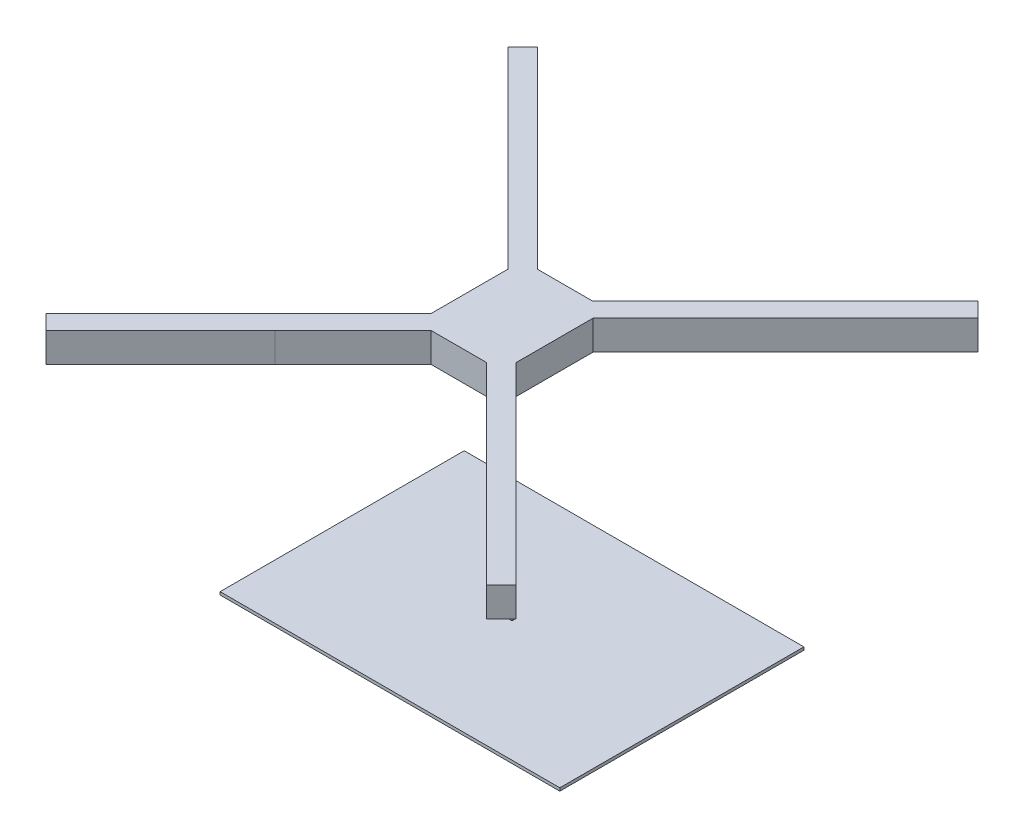
SolidWorks part; units mm, degrees
material "1060 Alloy"
ref_plane "Front" through (0, 0, 0) normal (0, 0, 1) x (1, 0, 0)
ref_plane "Top" through (0, 0, 0) normal (0, 1, 0) x (1, 0, 0)
ref_plane "Right" through (0, 0, 0) normal (1, 0, 0) x (0, 0, -1)
sketch "Sketch1" plane through (0, 0, 0) normal (0, 1, 0) x (1, 0, 0)
  line L0 (-37.7393, 72.1741) -> (-143.8053, 178.2401)
  line L5 (57.7393, -72.1741) -> (-57.7393, 72.1741) construction
  line L6 (57.7393, 72.1741) -> (-57.7393, -72.1741) construction
  line L8 (-163.8023, 158.2431) -> (-57.7393, 52.1741)
  line L9 (37.7393, 72.1741) -> (143.8053, 178.2401)
  line L11 (163.8023, 158.2431) -> (57.7393, 52.1741)
  line L12 (37.7393, -72.1741) -> (143.8053, -178.2401)
  line L14 (163.8023, -158.2431) -> (57.7393, -52.1741)
  line L15 (-57.7393, -52.1741) -> (-163.8023, -158.2431)
  line L17 (-143.8053, -178.2401) -> (-37.7393, -72.1741)
  line L18 (-57.7393, -52.1741) -> (-57.7393, 52.1741)
  line L19 (37.7393, 72.1741) -> (-37.7393, 72.1741)
  line L20 (-37.7393, -72.1741) -> (37.7393, -72.1741)
  line L21 (57.7393, 52.1741) -> (57.7393, -52.1741)
  line L34 (143.8053, -178.2401) -> (299.3688, -333.8036)
  line L35 (299.3688, -333.8036) -> (319.3658, -313.8066)
  line L36 (319.3658, -313.8066) -> (163.8023, -158.2431)
  line L37 (-163.8023, -158.2431) -> (-319.3613, -313.8111)
  line L38 (-319.3613, -313.8111) -> (-299.3638, -333.8075)
  line L39 (-143.8053, -178.2401) -> (-299.3638, -333.8075)
  line L40 (-143.8053, 178.2401) -> (-299.3688, 333.8036)
  line L41 (-299.3688, 333.8036) -> (-319.3658, 313.8066)
  line L42 (-163.8023, 158.2431) -> (-319.3658, 313.8066)
  line L43 (163.8023, 158.2431) -> (319.3613, 313.8111)
  line L44 (319.3613, 313.8111) -> (299.3638, 333.8075)
  line L45 (143.8053, 178.2401) -> (299.3638, 333.8075)
  point P0 (0, 0)
  dimension "D2" = 28.28
  dimension "D3" = 28.28
  dimension "D4" = 220
  dimension "D5" = 220
  dimension "D6" = 150
  dimension "D7" = 150
  dimension "D8" = 28.28
  dimension "D9" = 150
  dimension "D10" = 150
  dimension "D11" = 220
  dimension "D12" = 220
  dimension "D13" = 28.28
  dimension "D14" = 150
  dimension "D15" = 150
  dimension "D16" = 150
  dimension "D17" = 150
  dimension "D18" = 104.3482
extrude "Boss-Extrude1" add sketch "Sketch1" along normal blind 40
sketch "Sketch2" plane through (0, 0, 0) normal (0, -1, 0) x (-1, 0, 0)
  circle A0 centre (0, 0) radius 2
  dimension "D1" = 4
extrude "Boss-Extrude2" add sketch "Sketch2" along normal blind 317
sketch "Sketch3" plane through (0, -317, 0) normal (0, -1, 0) x (1, 0, 0)
  line L1 (230.7902, 165.813) -> (-230.7902, 165.813)
  line L2 (230.7902, 165.813) -> (230.7902, -165.813)
  line L3 (230.7902, -165.813) -> (-230.7902, -165.813)
  line L4 (-230.7902, 165.813) -> (-230.7902, -165.813)
  line L5 (230.7902, 165.813) -> (-230.7902, -165.813) construction
  line L6 (230.7902, -165.813) -> (-230.7902, 165.813) construction
  point P0 (0, 0)
extrude "Boss-Extrude3" add sketch "Sketch3" along normal blind 4
